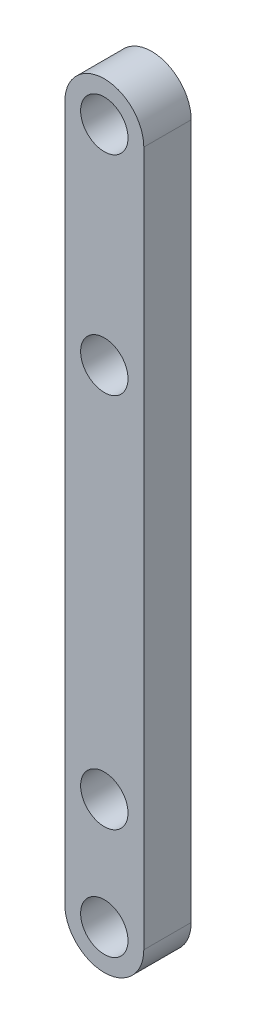
SolidWorks part; units mm, degrees
ref_plane "Front Plane" through (0, 0, 0) normal (0, 0, 1) x (1, 0, 0)
ref_plane "Top Plane" through (0, 0, 0) normal (0, 1, 0) x (1, 0, 0)
ref_plane "Right Plane" through (0, 0, 0) normal (1, 0, 0) x (0, 0, -1)
sketch "Sketch1" plane through (0, 0, 0) normal (0, 0, 1) x (1, 0, 0)
  line L0 (0, 0) -> (0, 440) construction
  line L1 (0, -55) -> (0, 55) construction
  line L2 (-25, 0) -> (-25, 440)
  line L3 (25, 0) -> (25, 440)
  arc A0 (-25, 0) -> (25, 0) centre (0, 0) ccw
  arc A1 (25, 440) -> (-25, 440) centre (0, 440) ccw
  circle A2 centre (0, 440) radius 15
  circle A3 centre (0, 308) radius 15
  circle A4 centre (0, 70) radius 15
  circle A5 centre (0, 0) radius 15
  point P5 (0, 220)
  dimension "D5" = 30
  dimension "D6" = 30
  dimension "D7" = 30
  dimension "D8" = 30
  dimension "D1" = 440
  dimension "D2" = 50
  dimension "D3" = 132
  dimension "D4" = 370
extrude "Boss-Extrude1" add sketch "Sketch1" along normal blind 30
